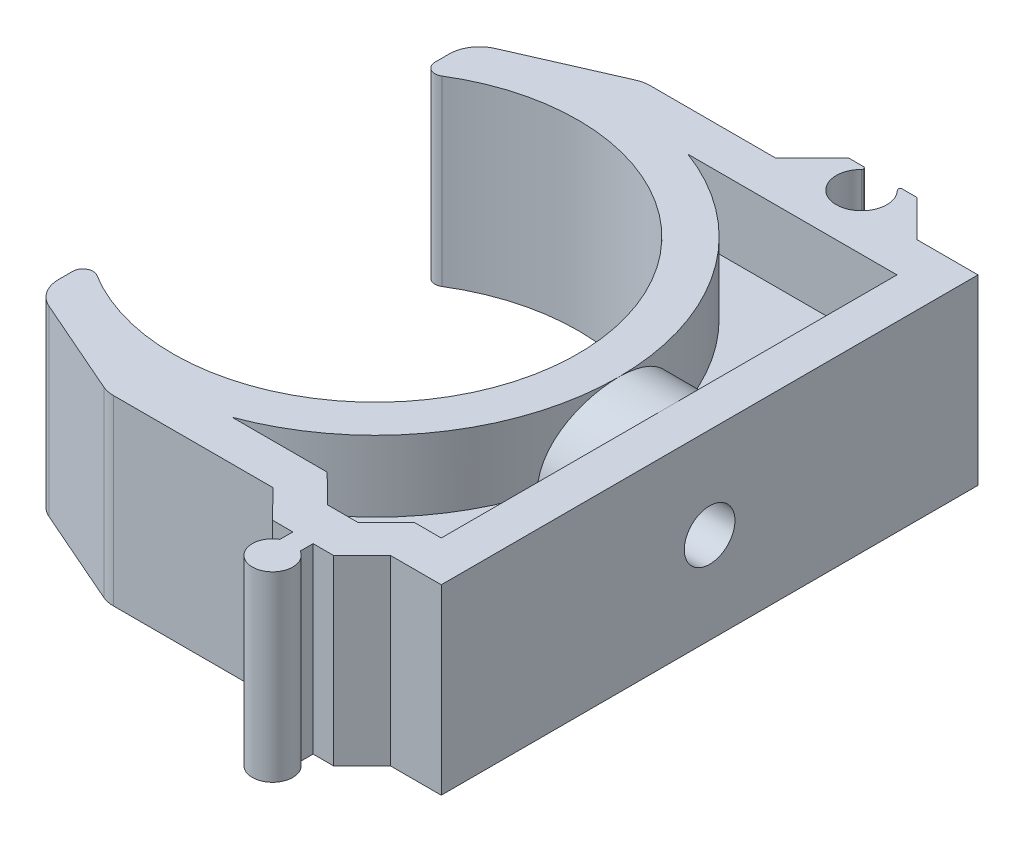
SolidWorks part; units mm, degrees
ref_plane "Front Plane" through (0, 0, 0) normal (0, 0, 1) x (1, 0, 0)
ref_plane "Top Plane" through (0, 0, 0) normal (0, 1, 0) x (1, 0, 0)
ref_plane "Right Plane" through (0, 0, 0) normal (1, 0, 0) x (0, 0, -1)
sketch "Sketch1" plane through (0, 0, 0) normal (0, 1, 0) x (1, 0, 0)
  line L0 (-22.5, -17.8885) -> (-22.5, -19.288)
  line L1 (-9.8708, 26.5) -> (2.5, 26.5)
  line L2 (-22.5, 19.2753) -> (-22.5, 17.8885)
  line L3 (-9.8725, -26.5) -> (5.88, -26.5)
  line L4 (22.5, 26.5) -> (22.5, -26.5)
  line L5 (-22.5, 26.5) -> (22.5, -26.5) construction
  line L6 (-22.5, -26.5) -> (22.5, 26.5) construction
  line L7 (22.5, 26.5) -> (16.5, 26.5)
  line L8 (-11.0749, -26.2485) -> (-20.7025, -22.0364)
  line L9 (-11.0762, 26.2472) -> (-20.7025, 22.0238)
  line L10 (-20.7025, 22.0238) -> (-20.7053, 22.0225)
  line L13 (16.5, 26.5) -> (22.5, 26.5)
  line L15 (7.5893, 30.1077) -> (6.1555, 30.1077)
  line L16 (6.1555, 30.1077) -> (2.5, 26.5)
  line L17 (11.4107, 30.1077) -> (12.8445, 30.1077)
  line L18 (12.8445, 30.1077) -> (16.5, 26.5)
  line L19 (22.5, -26.5) -> (17.5, -26.5)
  line L20 (17.5, -26.5) -> (14.653, -29.3097)
  line L21 (14.653, -29.3097) -> (12.653, -29.3097)
  line L22 (8.653, -29.3097) -> (5.88, -26.5)
  line L23 (10.653, -29.3097) -> (8.653, -29.3097)
  line L24 (17.5, -26.5) -> (22.5, -26.5)
  line L25 (10.653, -29.3097) -> (10.653, -30.5777)
  line L26 (12.653, -29.3097) -> (12.653, -30.5777)
  arc A0 (-20.9762, -17.0367) -> (-20.9762, 17.0367) centre (-10.5, 0) ccw
  arc A1 (-9.8725, -26.5) -> (-11.0749, -26.2485) centre (-9.8725, -23.5) cw
  arc A2 (-20.7025, -22.0364) -> (-22.5, -19.288) centre (-19.5, -19.288) cw
  arc A3 (-20.9762, -17.0367) -> (-22.5, -17.8885) centre (-21.5, -17.8885) ccw
  arc A4 (-20.9762, 17.0367) -> (-22.5, 17.8885) centre (-21.5, 17.8885) cw
  arc A5 (-20.7053, 22.0225) -> (-22.5, 19.2753) centre (-19.5, 19.2753) ccw
  arc A6 (-9.8708, 26.5) -> (-11.0762, 26.2472) centre (-9.8708, 23.5) ccw
  arc A7 (7.7308, 29.7664) -> (11.2692, 29.7664) centre (9.5, 28) ccw
  arc A8 (11.4107, 30.1077) -> (11.2692, 29.7664) centre (11.4107, 29.9077) ccw
  arc A9 (7.5893, 30.1077) -> (7.7308, 29.7664) centre (7.5893, 29.9077) cw
  arc A10 (10.653, -30.5777) -> (12.653, -30.5777) centre (11.653, -32.3097) ccw
  point P0 (0, 0)
  point P17 (-22.5, -16)
  point P36 (10.8445, 30.1077)
  point P39 (8.1555, 30.1077)
  dimension "D3" = 40
  dimension "D4" = 33
  dimension "D5" = 3
  dimension "D6" = 1
  dimension "D7" = 1
  dimension "D8" = 3
  dimension "D9" = 3
  dimension "D10" = 5
  dimension "D16" = 0.2
  dimension "D20" = 4
  dimension "D1" = 53
  dimension "D2" = 45
  dimension "D11" = 13
  dimension "D12" = 1.5
  dimension "D13" = 6
  dimension "D14" = 2
  dimension "D15" = 2
  dimension "D17" = 5
  dimension "D18" = 4
  dimension "D19" = 6
extrude "Boss-Extrude1" add sketch "Sketch1" along normal blind 18 contours L25 A10 L26 L21 L20 L19 L4 L7 L18 L17 A8 A7 A9 L15 L16 L1 A6 L9 L10 A5 L2 A4 A0 A3 L0 A2 L8 A1 L3 L22 L23
sketch "Sketch2" plane through (0, 0, 0) normal (0, -1, 0) x (1, 0, 0)
  line L0 (18.5, 22.5) -> (18.5, -22.5)
  line L1 (18.5, -22.5) -> (-2.1484, -22.5)
  line L2 (18.5, 22.5) -> (15.8433, 22.5)
  line L3 (22.5, 26.5) -> (17.5, 26.5) construction
  line L4 (22.5, -26.5) -> (22.5, 26.5) construction
  line L5 (22.5, -26.5) -> (16.5, -26.5) construction
  line L6 (7.2386, 22.5) -> (-2.1484, 22.5)
  line L9 (15.8433, 22.5) -> (13.0393, 25.2822)
  line L10 (13.0393, 25.2822) -> (10.0393, 25.282)
  line L11 (10.0393, 25.282) -> (7.2386, 22.5)
  arc A0 (-2.1484, -22.5) -> (-2.1484, 22.5) centre (-10.5, 0) ccw
  dimension "D1" = 48
  dimension "D2" = 4
  dimension "D3" = 4
  dimension "D4" = 4
  dimension "D5" = 3
  dimension "D6" = 3.9477
  dimension "D7" = 3.95
  dimension "D8" = 2.6567
extrude "Cut-Extrude1" cut sketch "Sketch2" against normal blind 7
ref_plane "Plane1" through (0, 9, 0) normal (0, -1, 0) x (-1, 0, 0)
mirror "Mirror1" about plane through (0, 9, 0) normal (0, -1, 0) of "Cut-Extrude1"
sketch "Sketch3" plane through (18.5, 0, 0) normal (-1, 0, 0) x (0, 0, 1)
  line L0 (-22.5, 7) -> (22.5, 7) construction
  line L1 (7, 7) -> (-7, 7)
  arc A0 (-7, 7) -> (7, 7) centre (0, 7) ccw
extrude "Boss-Extrude2" add sketch "Sketch3" along normal blind 7
mirror "Mirror2" about plane through (0, 9, 0) normal (0, -1, 0) of "Boss-Extrude2"
sketch "Sketch4" plane through (22.5, 0, 0) normal (1, 0, 0) x (0, 0, -1)
  circle A0 centre (0, 9) radius 2.5
  dimension "D1" = 5
extrude "Cut-Extrude2" cut sketch "Sketch4" against normal blind 6
ref_plane "Plane2" through (9.5, 0, 0) normal (1, 0, 0) x (0, 0, -1)
sketch "Sketch5" plane through (9.5, 0, 0) normal (1, 0, 0) x (0, 0, -1)
  line L7 (-24.75, 9) -> (24.75, 9) construction
  circle A0 centre (0, 9) radius 5.75
  point P0 (0, 9)
  dimension "D1" = 11.5
extrude "Cut-Extrude3" cut sketch "Sketch5" against normal blind 7
sketch "Sketch6" plane through (9.5, 0, 0) normal (-1, 0, 0) x (0, 0, 1)
  circle A0 centre (0, 9) radius 5.75
extrude "Cut-Extrude4" cut sketch "Sketch6" against normal blind 7
scale "Scale1" bodies to scale 108 scale about origin uniform scaling yes scale factor 0.75
scale "Scale2" bodies to scale 109 scale about origin uniform scaling yes scale factor 1.066667
